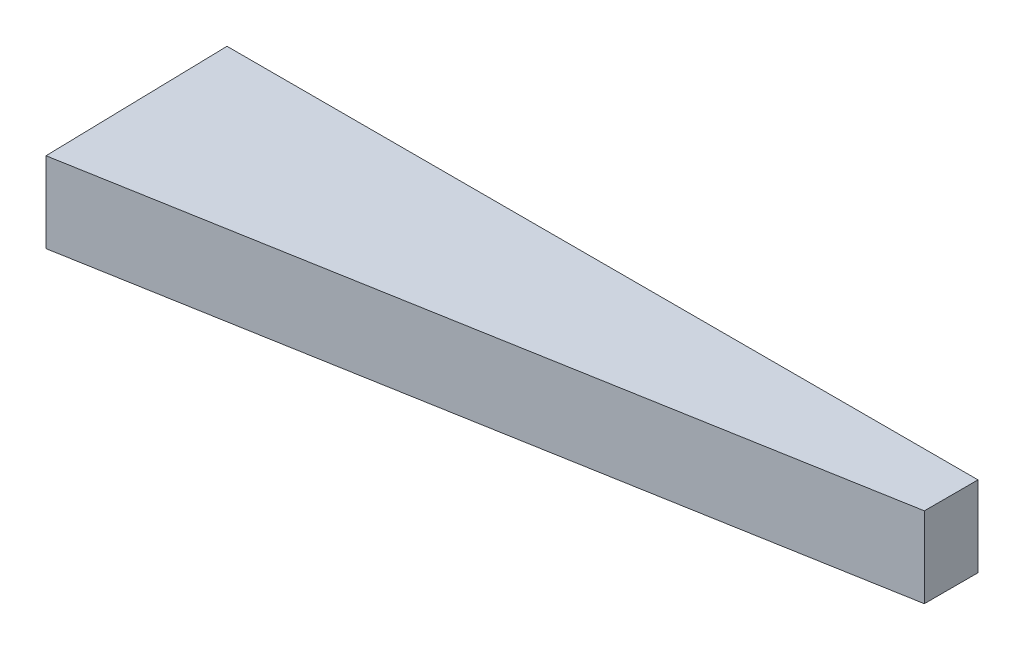
SolidWorks part; units mm, degrees
material "Pine"
ref_plane "Front Plane" through (0, 0, 0) normal (0, 0, 1) x (1, 0, 0)
ref_plane "Top Plane" through (0, 0, 0) normal (0, 1, 0) x (1, 0, 0)
ref_plane "Right Plane" through (0, 0, 0) normal (1, 0, 0) x (0, 0, -1)
sketch "Sketch1" plane through (0, 0, 0) normal (0, 1, 0) x (1, 0, 0)
  line L0 (0, 0) -> (177.8, 0)
  line L1 (177.8, 0) -> (177.8, -12.7)
  line L2 (177.8, -12.7) -> (1.017, -43.8716)
  line L3 (0, 0) -> (1.017, -43.8716)
  dimension "D1" = 177.8
  dimension "D2" = 12.7
  dimension "D3" = 10
extrude "Boss-Extrude1" add sketch "Sketch1" along normal blind 19.05
